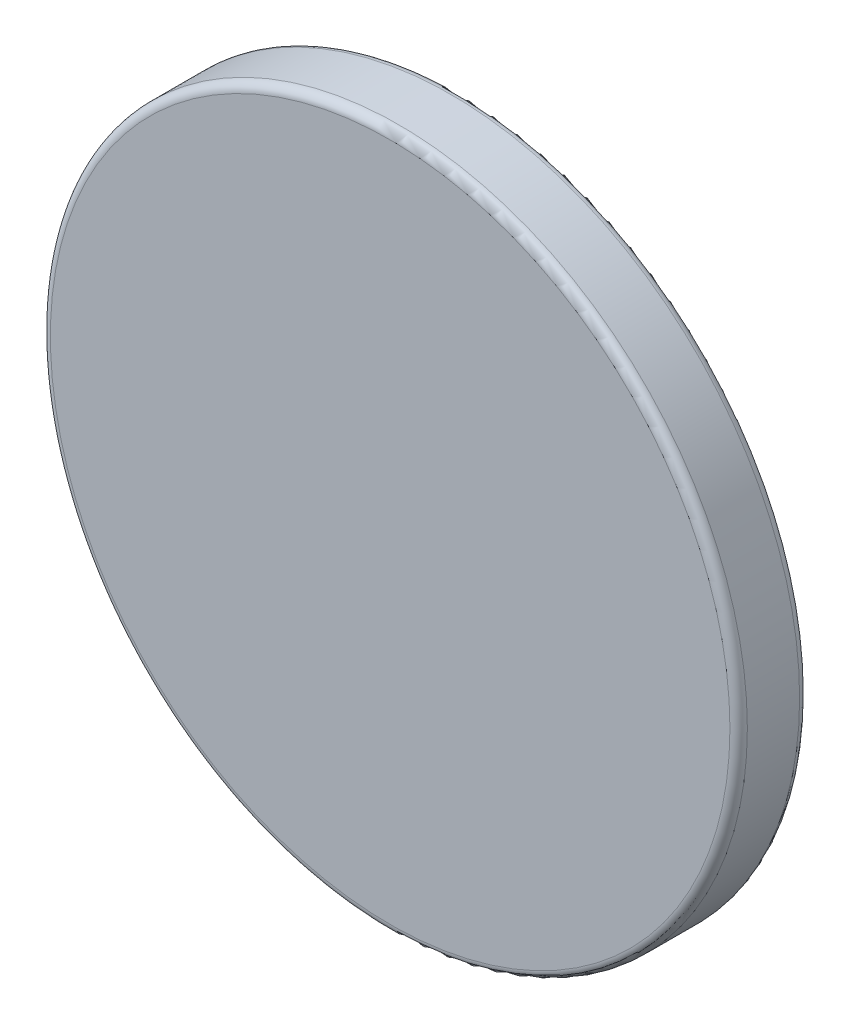
SolidWorks part; units mm, degrees
ref_plane "Plan de face" through (0, 0, 0) normal (0, 0, 1) x (1, 0, 0)
ref_plane "Plan de dessus" through (0, 0, 0) normal (0, 1, 0) x (1, 0, 0)
ref_plane "Plan de droite" through (0, 0, 0) normal (1, 0, 0) x (0, 0, -1)
sketch "Esquisse1" plane through (0, 0, 0) normal (0, 0, 1) x (1, 0, 0)
  circle A0 centre (0, 0) radius 10
  dimension "D1" = 20
extrude "Boss.-Extru.1" add sketch "Esquisse1" along normal blind 2
fillet "Congé1" radius 0.25 2 edges at (10, 0, 0) (10, 0, 2)
